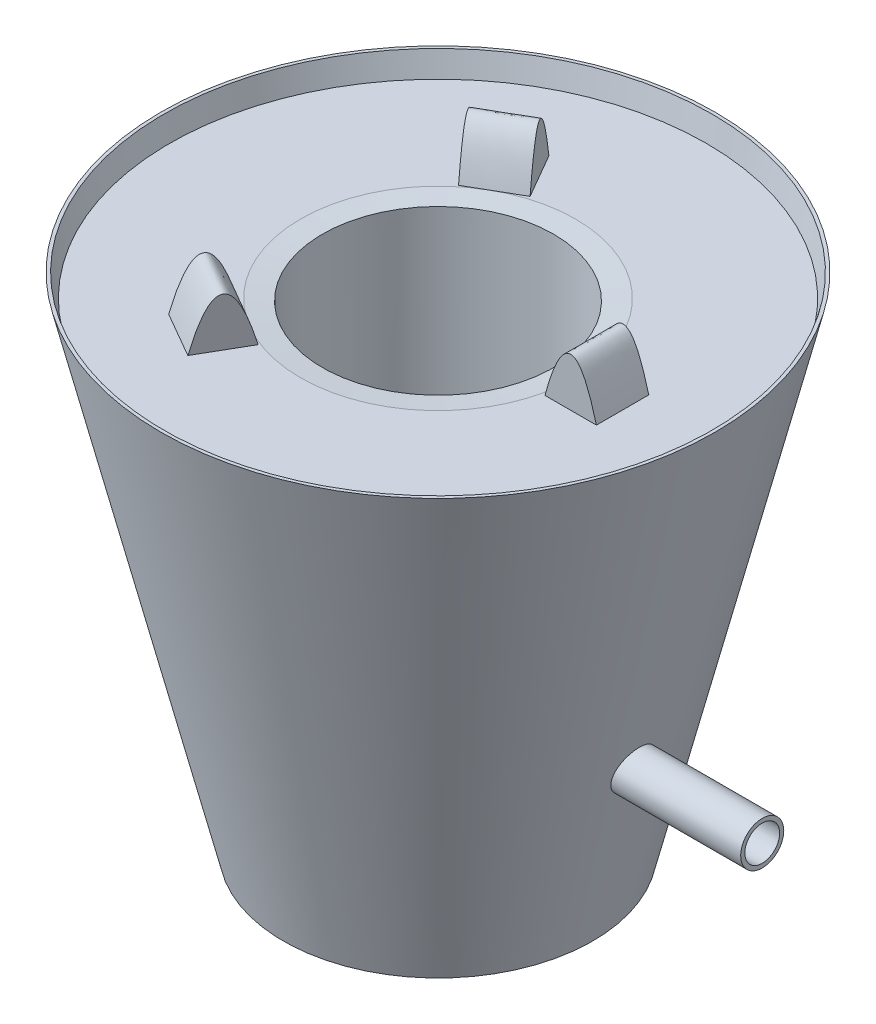
SolidWorks part; units mm, degrees
ref_plane "Front Plane" through (0, 0, 0) normal (0, 0, 1) x (1, 0, 0)
ref_plane "Top Plane" through (0, 0, 0) normal (0, 1, 0) x (1, 0, 0)
ref_plane "Right Plane" through (0, 0, 0) normal (1, 0, 0) x (0, 0, -1)
sketch "Sketch1" plane through (0, 0, 0) normal (0, 1, 0) x (1, 0, 0)
  circle A0 centre (0, 0) radius 127
ref_plane "Plane1" through (0, -230, 0) normal (0, 1, 0) x (1, 0, 0)
sketch "Sketch2" plane through (0, -230, 0) normal (0, 1, 0) x (1, 0, 0)
  circle A0 centre (0, 0) radius 70.9009
sketch "Sketch3" plane through (0, 0, 0) normal (0, 0, 1) x (1, 0, 0)
  line L0 (0, -230) -> (0, 0) construction
  line L1 (70.9009, -230) -> (-70.9009, -230) construction
  line L2 (70.9009, -230) -> (127, 0)
  line L3 (127, 0) -> (-127, 0) construction
  line L4 (0, -229.082) -> (69.9175, -229.082)
  line L5 (69.9175, -229.082) -> (122.7719, -11.3989)
  line L6 (125.2338, -1.2594) -> (125.5396, 0)
  line L7 (125.5396, 0) -> (127, 0)
  line L8 (70.9009, -230) -> (0, -230)
  line L9 (0, -230) -> (0, -229.082)
  line L10 (123.0108, -10.4148) -> (63.0108, -10.4148)
  line L11 (122.7719, -11.3989) -> (54.7697, -11.3989)
  line L12 (52.9779, -11.3989) -> (63.0108, -10.4148)
  line L13 (123.0108, -10.4148) -> (125.2338, -1.2594)
  line L14 (52.9779, -11.3989) -> (52.9779, -105.4156)
  line L15 (52.9779, -105.4156) -> (29.9495, -105.4156)
  line L16 (29.9495, -105.4156) -> (29.9495, -165.4156)
  line L17 (29.9495, -165.4156) -> (0, -165.4156)
  line L18 (54.7697, -11.3989) -> (54.7697, -106.7241)
  line L19 (54.7697, -106.7241) -> (31.4607, -106.7241)
  line L20 (31.4607, -106.7241) -> (31.4607, -167.0217)
  line L21 (31.4607, -167.0217) -> (0, -167.0217)
  line L22 (0, -167.0217) -> (0, -165.4156)
revolve "Revolve1" add sketch "Sketch3" angle 360 about L0
ref_plane "Plane2" through (0, -200, 0) normal (0, 1, 0) x (1, 0, 0)
sketch "Sketch4" plane through (0, -200, 0) normal (0, 1, 0) x (1, 0, 0)
  circle A0 centre (0, 0) radius 74.5397
extrude "Boss-Extrude1" add sketch "Sketch4" along normal blind 3 separate body
sketch "Sketch5" plane through (0, 0, 0) normal (0, 1, 0) x (1, 0, 0)
  circle A0 centre (0, 0) radius 125.5396
  circle A1 centre (0, 0) radius 67
ref_plane "Plane3" through (138.5661, 0, 0) normal (1, 0, 0) x (0, 0, -1)
sketch "Sketch6" plane through (138.5661, 0, 0) normal (1, 0, 0) x (0, 0, -1)
  circle A0 centre (0, -152.314) radius 9.8675
  circle A1 centre (0, -152.314) radius 7.9764
extrude "Boss-Extrude2" add sketch "Sketch6" against normal blind 100 and the other way blind 10
ref_plane "Plane4" through (0, 0, -143.1141) normal (0, 0, 1) x (1, 0, 0)
sketch "Sketch7" plane through (0, 0, -143.1141) normal (0, 0, 1) x (1, 0, 0)
  circle A0 centre (0, -30.7537) radius 12.7
sketch "Sketch8" plane through (0, 0, 0) normal (0, 0, 1) x (1, 0, 0)
  line L1 (86.5882, 11.8263) -> (63.0108, 11.8263) construction
  line L2 (86.5882, 11.8263) -> (86.5882, -10.4148) construction
  line L3 (86.5882, -10.4148) -> (63.0108, -10.4148)
  line L4 (63.0108, 11.8263) -> (63.0108, -10.4148) construction
  spline S0 degree 2 poles (86.5882, -10.4148) (74.7995, 34.0674) (63.0108, -10.4148) knots 0 0 0 1 1 1
extrude "Boss-Extrude3" add sketch "Sketch8" along normal blind 14 and the other way blind 10
pattern_circular "CirPattern1" count 3 over 360 about axis through (0, -10.4148, 0) along (0, -1, 0) of "Boss-Extrude3"
